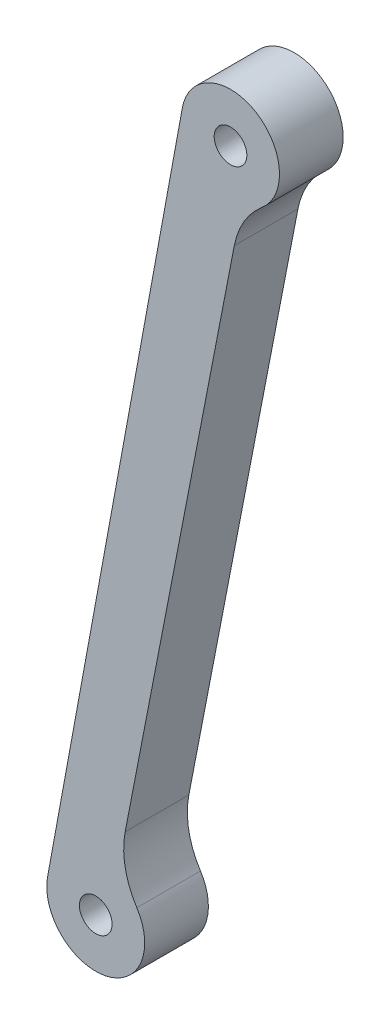
SolidWorks part; units mm, degrees
ref_plane "Спереди" through (0, 0, 0) normal (0, 0, 1) x (1, 0, 0)
ref_plane "Сверху" through (0, 0, 0) normal (0, 1, 0) x (1, 0, 0)
ref_plane "Справа" through (0, 0, 0) normal (1, 0, 0) x (0, 0, -1)
sketch "Sketch5" plane through (0, 0, 0) normal (0, 0, 1) x (1, 0, 0)
  line L0 (1.7523, 0.4742) -> (37.3029, 86.8114) construction
  line L1 (-1.0106, -0.6044) -> (29.6618, 87.5839) construction
  line L2 (0, 0) -> (17.8901, 43.1295)
  line L3 (0, 0) -> (114.3643, 0) construction
  line L4 (23.8823, 39.6684) -> (24.5035, 51.2503)
  line B0 (17.4507, 115.16) -> (29.9551, 112.6983)
  spline B1 degree 3 poles (29.9551, 112.6983) (28.321, 116.0983) (27.9284, 121.1676) (30.1713, 134.4746) (29.8473, 132.0116) (30.6222, 139.9349) (27.0176, 140.9027) knots 0 0 0 0 0.297085 0.369784 0.687298 1 1 1 1
  spline B2 degree 2 poles (27.0176, 140.9027) (20.5603, 128.6427) (17.4507, 115.16) knots 0 0 0 1 1 1
  spline B3 degree 2 poles (27.0176, 140.9027) (26.5004, 134.6878) (22.2537, 130.5645) knots 0 0 0 1 1 1
  line B4 (17.1977, 114.3508) -> (29.842, 112.2111)
  line B5 (28.7001, 84.8969) -> (10.3668, 87.513)
  spline B6 degree 1 poles (17.1977, 114.3508) (10.3668, 87.513) knots 0 0 1 1
  spline B7 degree 2 poles (29.842, 112.2111) (22.5534, 98.8452) (28.7001, 84.8969) knots 0 0 0 1 1 1
  line B8 (10.1904, 87.4159) -> (28.2572, 84.4958)
  line B9 (32.8909, 45.7292) -> (10.0695, 42.8593)
  spline B10 degree 2 poles (10.1904, 87.4159) (10.0234, 65.1379) (10.0695, 42.8593) knots 0 0 0 1 1 1
  spline B11 degree 2 poles (28.2572, 84.4958) (20.6417, 64.1094) (32.8909, 45.7292) knots 0 0 0 1 1 1
  line B12 (10.2797, 36.8758) -> (3.9253, -13.9853)
  line B13 (3.9253, -13.9853) -> (33.9594, -31.0804)
  line B14 (33.9594, -31.0804) -> (45.9193, -27.7969)
  line B15 (45.9193, -27.7969) -> (58.2918, -13.9853)
  line B16 (58.2918, -13.9853) -> (69.0331, -4.9875)
  line B17 (69.0331, -4.9875) -> (82.514, 2.0236)
  line B18 (82.514, 2.0236) -> (89.2736, 3.8794)
  line B19 (89.2736, 3.8794) -> (92.4846, 9.5208)
  line B20 (92.4846, 9.5208) -> (96.8914, 17.263)
  line B21 (96.8914, 17.263) -> (101.4978, 21.1217)
  line B22 (101.4978, 21.1217) -> (103.9241, 23.1541)
  line B23 (104.261, 27.4157) -> (104.5375, 25.5318)
  line B24 (84.192, 21.2056) -> (87.7484, 22.7822)
  line B25 (87.7484, 22.7822) -> (92.912, 27.4956)
  line B26 (71.6086, 15.6268) -> (84.192, 21.2056)
  line B27 (92.912, 27.4956) -> (95.357, 29.7274)
  line B28 (95.357, 29.7274) -> (96.8049, 29.9399)
  line B29 (71.6086, 15.6268) -> (53.4239, 15.2713)
  line B30 (48.0904, 17.5622) -> (39.9394, 26.4919)
  line B31 (39.9394, 26.4919) -> (33.9594, 37.99)
  line B32 (33.9594, 37.99) -> (10.2797, 36.8758)
  line B33 (96.8049, 29.9399) -> (99.4078, 30.2175)
  line B34 (99.4078, 30.2175) -> (102.2786, 29.261)
  line B35 (102.2786, 29.261) -> (104.261, 27.4157)
  line B36 (104.5375, 25.5318) -> (103.9241, 23.1541)
  arc B37 (53.4239, 15.2713) -> (48.0904, 17.5622) centre (53.2864, 22.3051) cw
  spline B38 degree 3 poles (104.261, 27.4157) (103.5289, 27.0494) (99.8378, 26.2685) (94.8982, 17.2338) (98.6516, 18.7375) knots 0 0 0 0 0.441207 1 1 1 1
  line B39 (27.7375, 116.5129) -> (14.1959, 87.8955)
  line B40 (27.7375, 116.5129) -> (25.9485, 114.8372)
  line B41 (25.9485, 114.8372) -> (27.5763, 114.067)
  line B42 (27.7375, 116.5129) -> (27.5763, 114.067)
  line B43 (26.1527, 88.0864) -> (17.8901, 43.1295)
  line B44 (19.3622, 85.005) -> (23.8823, 39.6684)
  line B45 (19.3622, 85.005) -> (17.7584, 73.9508)
  line B46 (17.7584, 73.9508) -> (23.117, 74.485)
  line B47 (23.117, 74.485) -> (19.3622, 85.005)
  line B48 (26.1527, 88.0864) -> (23.7481, 82.7635)
  line B49 (23.7481, 82.7635) -> (25.1278, 82.5099)
  line B50 (25.1278, 82.5099) -> (26.5087, 82.2561)
  line B51 (26.5087, 82.2561) -> (26.1527, 88.0864)
  line B52 (26.1527, 88.0864) -> (19.3622, 85.005)
  line B53 (19.3622, 85.005) -> (22.3683, 87.7853)
  line B54 (22.3683, 87.7853) -> (22.9012, 86.6109)
  line B55 (22.9012, 86.6109) -> (23.4998, 85.2917)
  line B56 (23.4998, 85.2917) -> (19.3622, 85.005)
  dimension "D1" = 93.37
  dimension "D2" = 93.37
  dimension "D4" = 67.471
  dimension "D5" = 8.764
sketch_block_instance "Block1-1"
sketch_block "Block1"
sketch_block_instance "Block2-1"
sketch_block "Block2"
sketch_block_instance "Block3-1"
sketch_block "Block3"
sketch_block_instance "Block18-1"
sketch_block "Block18"
sketch_block_instance "Block44-1"
sketch_block "Block44"
sketch_block_instance "Block46-1"
sketch_block "Block46"
sketch_block_instance "Block47-1"
sketch_block "Block47"
sketch_block_instance "Block48-1"
sketch_block "Block48"
sketch_block_instance "Block50-1"
sketch_block "Block50"
sketch "Sketch7" plane through (0, 0, 0) normal (0, 0, 1) x (1, 0, 0)
  line L0 (14.9395, 43.6718) -> (23.1953, 88.5924)
  line L1 (19.6932, 48.436) -> (26.3767, 82.8719)
  arc A0 (14.9395, 43.6718) -> (20.4069, 44.7622) centre (17.8901, 43.1295) ccw
  arc A1 (28.0731, 85.7511) -> (23.1953, 88.5924) centre (26.1459, 88.0502) ccw
  circle A2 centre (17.8901, 43.1295) radius 1
  circle A3 centre (26.1459, 88.0502) radius 1
  arc A4 (26.3767, 82.8719) -> (28.0731, 85.7511) centre (31.2851, 81.9192) cw
  arc A5 (19.6932, 48.436) -> (20.4069, 44.7622) centre (24.6016, 47.4833) ccw
  dimension "D1" = 2
  dimension "D2" = 6
  dimension "D3" = 5
extrude "Boss-Extrude2" add sketch "Sketch7" along normal blind 3.9
sketch "Sketch8" plane through (0, 0, 3.9) normal (0, 0, 1) x (1, 0, 0)
  line L0 (26.1459, 91.0502) -> (26.1459, 89.0502)
  line L1 (26.1459, 87.0502) -> (26.1459, 85.0502)
  arc A0 (26.1459, 85.0502) -> (26.1459, 91.0502) centre (26.1459, 88.0502) ccw
  arc A1 (26.1459, 87.0502) -> (26.1459, 89.0502) centre (26.1459, 88.0502) ccw
